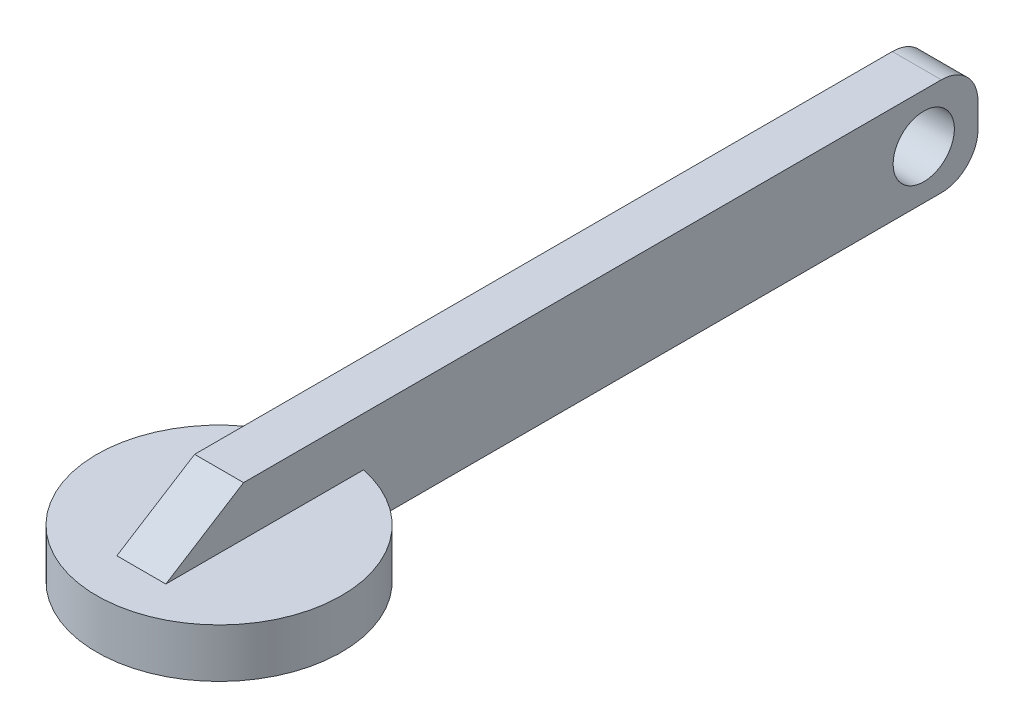
SolidWorks part; units mm, degrees
ref_plane "Front Plane" through (0, 0, 0) normal (0, 0, 1) x (1, 0, 0)
ref_plane "Top Plane" through (0, 0, 0) normal (0, 1, 0) x (1, 0, 0)
ref_plane "Right Plane" through (0, 0, 0) normal (1, 0, 0) x (0, 0, -1)
sketch "Sketch1" plane through (0, 0, 0) normal (0, 1, 0) x (1, 0, 0)
  line L1 (-2, -30) -> (2, -30)
  line L2 (-2, -30) -> (-2, 30)
  line L3 (-2, 30) -> (2, 30)
  line L4 (2, -30) -> (2, 30)
  line L5 (-2, -30) -> (2, 30) construction
  line L6 (-2, 30) -> (2, -30) construction
  point P0 (0, 0)
  dimension "D1" = 4
  dimension "D2" = 60
extrude "Boss-Extrude1" add sketch "Sketch1" along normal blind 8
sketch "Sketch2" plane through (-2, 0, 0) normal (-1, 0, 0) x (0, 0, 1)
  circle A0 centre (-25.5676, 4) radius 2.5
  dimension "D1" = 5
extrude "Cut-Extrude1" cut sketch "Sketch2" against normal blind 8
fillet "Fillet1" radius 3 2 edges at (0, 8, -30) (0, 0, -30)
sketch "Sketch3" plane through (0, 0, 0) normal (0, -1, 0) x (1, 0, 0)
  line L0 (-2, 30) -> (2, 30) construction
  circle A0 centre (0, 30) radius 10
  dimension "D1" = 20
extrude "Boss-Extrude2" add sketch "Sketch3" against normal blind 4
sketch "Sketch4" plane through (2, 0, 0) normal (1, 0, 0) x (0, 0, -1)
  line L0 (-30, 4) -> (-36.3517, 4)
  line L1 (-36.3517, 4) -> (-30, 8)
  line L2 (-30, 8) -> (-30, 4)
extrude "Boss-Extrude3" add sketch "Sketch4" against normal blind 4
